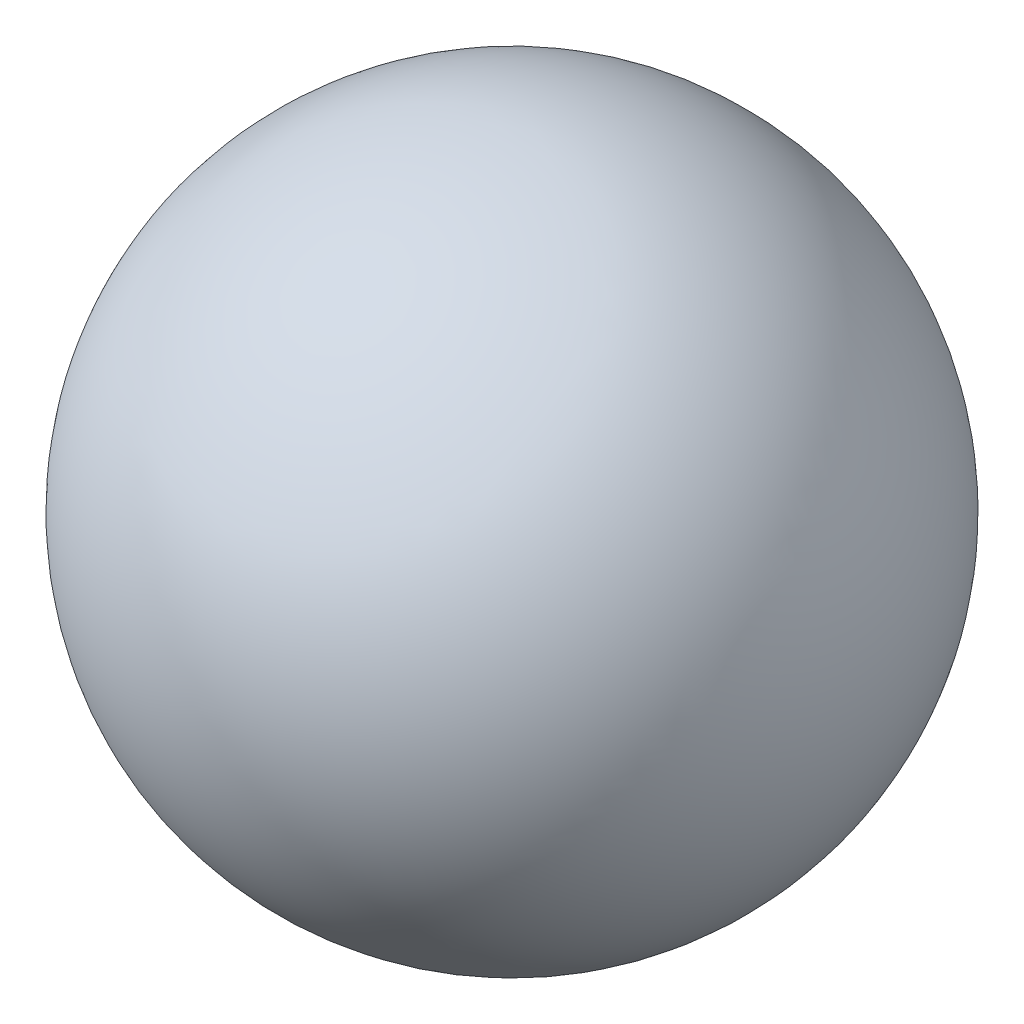
SolidWorks part; units mm, degrees
ref_plane "Alzado" through (0, 0, 0) normal (0, 0, 1) x (1, 0, 0)
ref_plane "Planta" through (0, 0, 0) normal (0, 1, 0) x (1, 0, 0)
ref_plane "Vista lateral" through (0, 0, 0) normal (1, 0, 0) x (0, 0, -1)
sketch "Croquis1" plane through (0, -2.4739, 0) normal (0, 1, 0) x (1, 0, 0)
  line L0 (28.1804, -21.8339) -> (-9.8196, -21.8339)
  arc A0 (28.1804, -21.8339) -> (-9.8196, -21.8339) centre (9.1804, -21.8339) ccw
  dimension "D1" = 38
revolve "Revolución2" add sketch "Croquis1" angle 360 about L0
